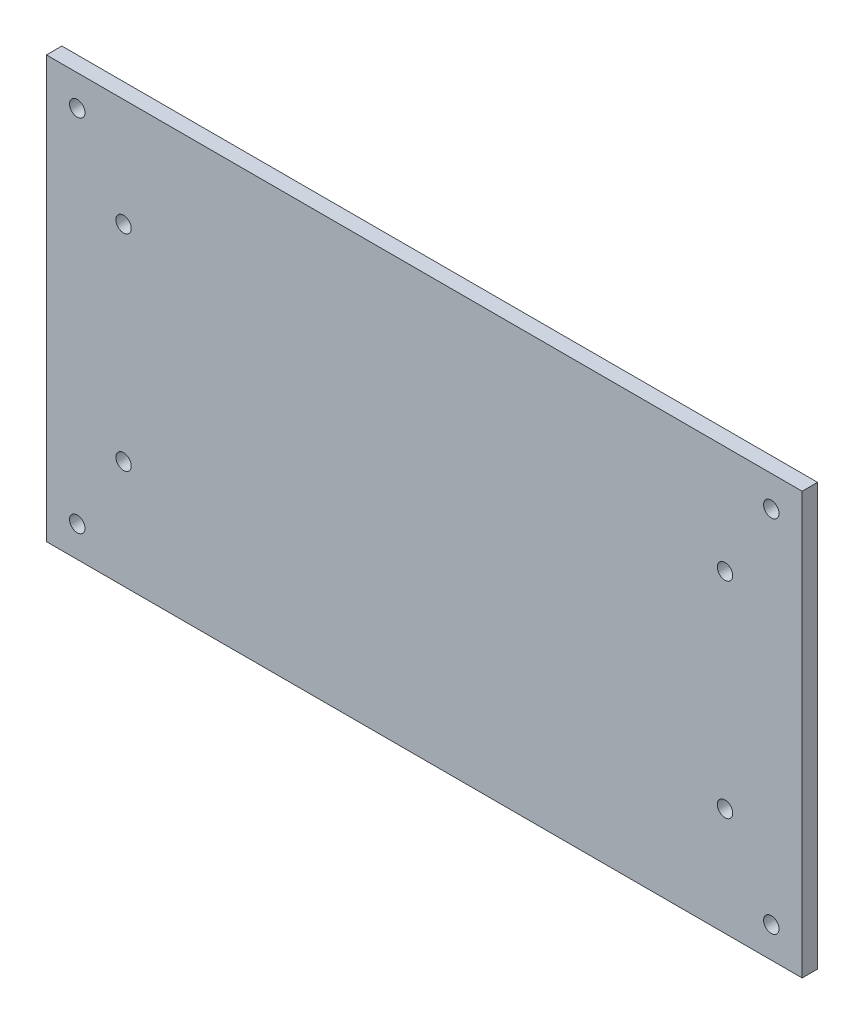
SolidWorks part; units mm, degrees
ref_plane "前视基准面" through (0, 0, 0) normal (0, 0, 1) x (1, 0, 0)
ref_plane "上视基准面" through (0, 0, 0) normal (0, 1, 0) x (1, 0, 0)
ref_plane "右视基准面" through (0, 0, 0) normal (1, 0, 0) x (0, 0, -1)
sketch "草图1" plane through (0, 0, 0) normal (0, 0, 1) x (1, 0, 0)
  line L0 (-76.9745, -5.4527) -> (70.0255, -5.4527) construction
  line L1 (-76.9745, 35.5473) -> (70.0255, 35.5473)
  line L2 (-76.9745, 35.5473) -> (-76.9745, -46.4527)
  line L3 (-76.9745, -46.4527) -> (70.0255, -46.4527)
  line L4 (70.0255, 35.5473) -> (70.0255, -46.4527)
  line L5 (-3.4745, -46.4527) -> (-3.4745, 35.5473) construction
  circle A0 centre (-70.9745, 29.5473) radius 1.5
  circle A1 centre (64.0255, 29.5473) radius 1.5
  circle A2 centre (64.0255, -40.4527) radius 1.5
  circle A3 centre (-70.9745, -40.4527) radius 1.5
  dimension "D3" = 3
  dimension "D1" = 147
  dimension "D2" = 82
  dimension "D4" = 6
  dimension "D5" = 6
extrude "凸台-拉伸1" add sketch "草图1" along normal blind 3
sketch "草图2" plane through (0, 0, 0) normal (0, 0, -1) x (-1, 0, 0)
  line L0 (-70.0255, -46.4527) -> (-70.0255, 35.5473) construction
  line L1 (-70.0255, 35.5473) -> (76.9745, 35.5473) construction
  line L2 (76.9745, -46.4527) -> (-70.0255, -46.4527) construction
  line L3 (76.9745, 35.5473) -> (76.9745, -46.4527) construction
  circle A0 centre (-55.0255, 14.5473) radius 1.5
  circle A1 centre (-55.0255, -25.4527) radius 1.5
  circle A2 centre (61.9745, -25.4527) radius 1.5
  circle A3 centre (61.9745, 14.5473) radius 1.5
  dimension "D6" = 3
  dimension "D7" = 3
  dimension "D8" = 3
  dimension "D9" = 3
  dimension "D1" = 40
  dimension "D2" = 15
  dimension "D3" = 15
  dimension "D4" = 21
  dimension "D5" = 21
  dimension "D10" = 21
  dimension "D11" = 40
  dimension "D12" = 21
  dimension "D13" = 15
  dimension "D14" = 15
extrude "切除-拉伸1" cut sketch "草图2" against normal blind 3
